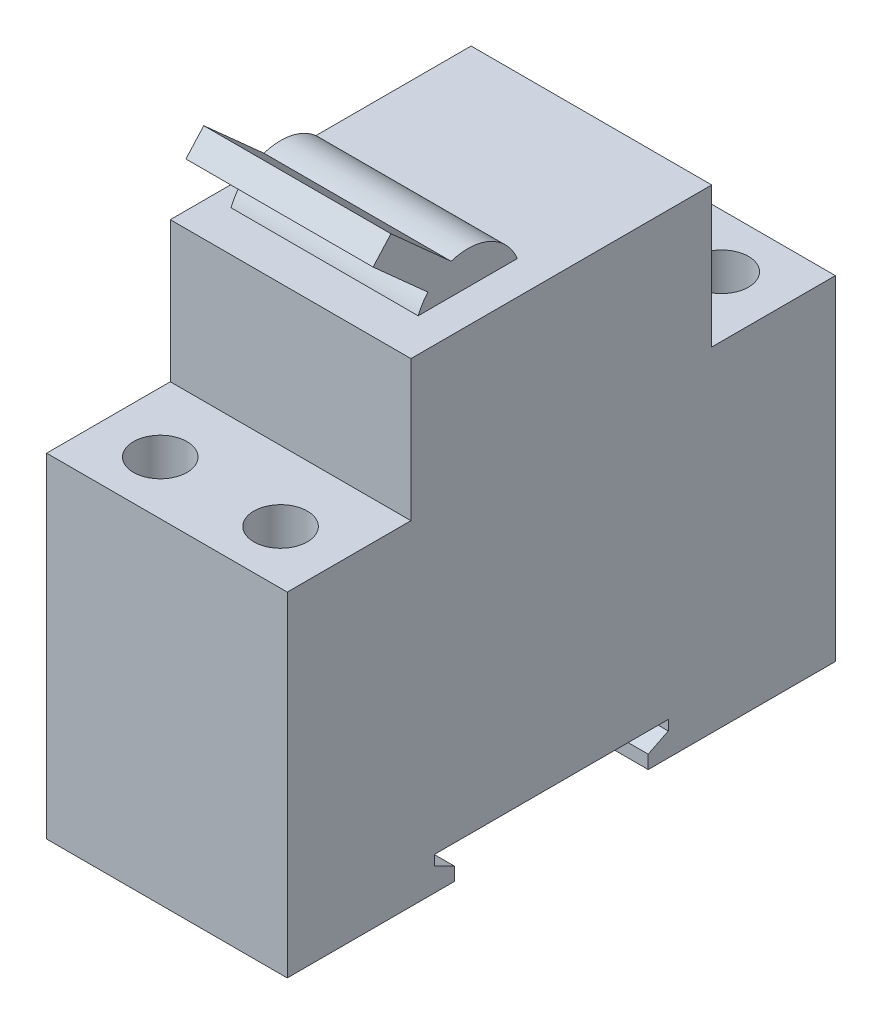
SolidWorks part; units mm, degrees
material "PW80:Mi:0:30:C1:0:1:2:Re:16:De:1:35:"
ref_plane "Plan1" through (0, 0, 0) normal (0, 0, 1) x (1, 0, 0)
ref_plane "Plan2" through (0, 0, 0) normal (0, 1, 0) x (1, 0, 0)
ref_plane "Plan3" through (0, 0, 0) normal (1, 0, 0) x (0, 0, -1)
sketch "Esquisse1" plane through (0, 0, 0) normal (1, 0, 0) x (0, 0, -1)
  line L0 (0, 0) -> (0, 50)
  line L1 (0, 0) -> (25, 0)
  line L2 (25, 0) -> (25, 2)
  line L3 (25, 2) -> (22, 3.5)
  line L4 (22, 3.5) -> (22, 5)
  line L5 (22, 5) -> (57, 5)
  line L6 (57, 5) -> (57, 3.5)
  line L7 (57, 3.5) -> (54, 2)
  line L8 (54, 2) -> (54, 0)
  line L9 (0, 50) -> (18.5, 50)
  line L10 (18.5, 50) -> (18.5, 71)
  line L11 (18.5, 71) -> (63.5, 71)
  line L12 (63.5, 71) -> (63.5, 50)
  line L13 (63.5, 50) -> (82, 50)
  line L14 (82, 50) -> (82, 0)
  line L15 (82, 0) -> (54, 0)
extrude "Base-Extrusion" add sketch "Esquisse1" along normal blind 36
ref_plane "Plan4" through (3, 0, 0) normal (1, 0, 0) x (0, 0, -1)
sketch "Esquisse5" plane through (3, 0, 0) normal (1, 0, 0) x (0, 0, -1)
  line L0 (26.0421, 73.3389) -> (17.8396, 80.6893)
  line L1 (17.8396, 80.6893) -> (20.5108, 83.6701)
  line L2 (20.5108, 83.6701) -> (29.5126, 75.6035)
  line L3 (24, 68) -> (40, 68)
  arc A0 (24, 68) -> (26.0421, 73.3389) centre (32, 68) cw
  arc A1 (29.5126, 75.6035) -> (40, 68) centre (32, 68) cw
extrude "Boss.-Extru.3" add sketch "Esquisse5" along normal blind 28
sketch "Esquisse6" plane through (0, 50, 0) normal (0, 1, 0) x (-1, 0, 0)
  circle A0 centre (-9, -8) radius 4
  circle A1 centre (-27, -8) radius 4
  circle A2 centre (-45, -8) radius 4
  circle A3 centre (-63, -8) radius 4
  circle A4 centre (-9, -74) radius 4
  circle A5 centre (-27, -74) radius 4
  circle A6 centre (-45, -74) radius 4
  circle A7 centre (-63, -74) radius 4
extrude "Enlèv. mat.-Extru.2" cut sketch "Esquisse6" against normal blind 10
